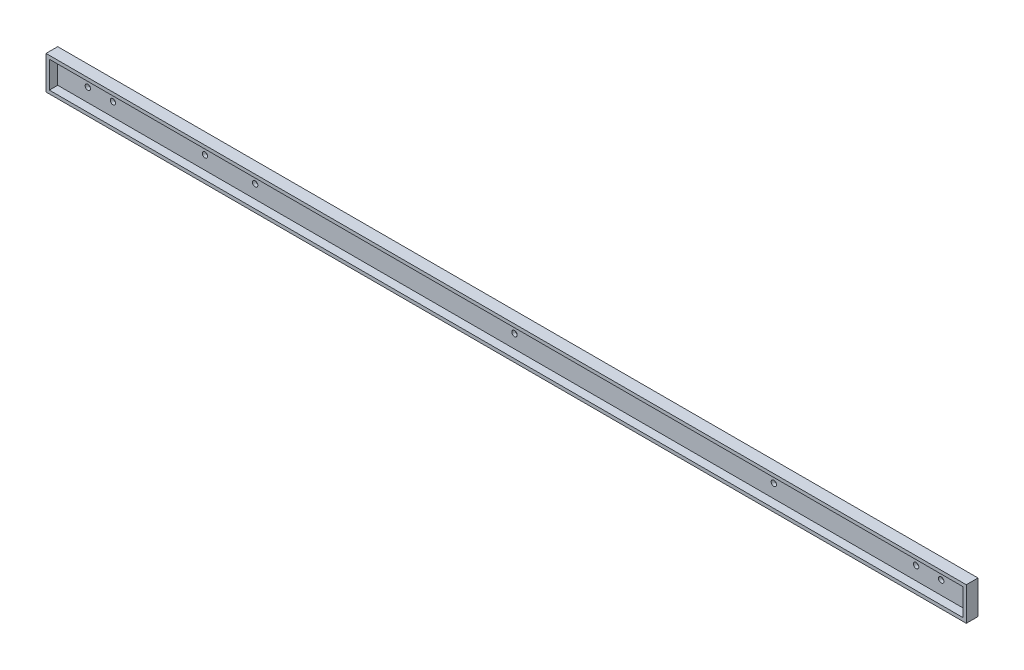
SolidWorks part; units mm, degrees
ref_plane "正面" through (0, 0, 0) normal (0, 0, 1) x (1, 0, 0)
ref_plane "平面" through (0, 0, 0) normal (0, 1, 0) x (1, 0, 0)
ref_plane "右側面" through (0, 0, 0) normal (1, 0, 0) x (0, 0, -1)
sketch "ｽｹｯﾁ1" plane through (0, 0, 0) normal (0, 0, 1) x (1, 0, 0)
  line L1 (-275, 10) -> (275, 10)
  line L2 (-275, 10) -> (-275, -10)
  line L3 (-275, -10) -> (275, -10)
  line L4 (275, 10) -> (275, -10)
  line L5 (-275, 10) -> (275, -10) construction
  line L6 (-275, -10) -> (275, 10) construction
  point P0 (0, 0)
  dimension "D1" = 550
  dimension "D2" = 20
extrude "ﾎﾞｽ - 押し出し1" add sketch "ｽｹｯﾁ1" along normal blind 7
sketch "ｽｹｯﾁ2" plane through (0, 0, 7) normal (0, 0, 1) x (1, 0, 0)
  line L14 (273, -8) -> (273, 8)
  line L15 (-273, 8) -> (-273, -8)
  line L16 (-273, -8) -> (273, -8)
  line L17 (273, 8) -> (-273, 8)
  line L18 (273, -8) -> (273, 8)
  line L19 (-273, 8) -> (-273, -8)
  line L20 (-273, -8) -> (273, -8)
  line L21 (273, 8) -> (-273, 8)
  dimension "D1" = 2
extrude "ｶｯﾄ - 押し出し1" cut sketch "ｽｹｯﾁ2" against normal blind 5
sketch "ｽｹｯﾁ3" plane through (0, 0, 0) normal (0, 0, -1) x (-1, 0, 0)
  line L0 (3.85, 0) -> (-3.85, 0) construction
  line L1 (275, 10) -> (275, -10) construction
  line L2 (0, 3.85) -> (0, -3.85) construction
  circle A0 centre (255, 0) radius 1.6
  circle A1 centre (240, 0) radius 1.6
  circle A2 centre (155, 0) radius 1.6
  circle A3 centre (0, 0) radius 1.6
  circle A4 centre (-255, 0) radius 1.6
  circle A5 centre (-240, 0) radius 1.6
  circle A6 centre (-155, 0) radius 1.6
  dimension "D1" = 3.2
  dimension "D2" = 3.2
  dimension "D3" = 3.2
  dimension "D4" = 20
  dimension "D5" = 35
  dimension "D6" = 120
  dimension "D7" = 3.2
extrude "ｶｯﾄ - 押し出し2" cut sketch "ｽｹｯﾁ3" against normal through all
sketch "ｽｹｯﾁ4" plane through (0, 0, 0) normal (0, 0, -1) x (-1, 0, 0)
  line L0 (3.85, 0) -> (-3.85, 0) construction
  circle A0 centre (185, 0) radius 1.6
  circle A1 centre (255, 0) radius 1.6 construction
  dimension "D1" = 3.2
  dimension "D2" = 70
extrude "ｶｯﾄ - 押し出し3" cut sketch "ｽｹｯﾁ4" against normal through all
